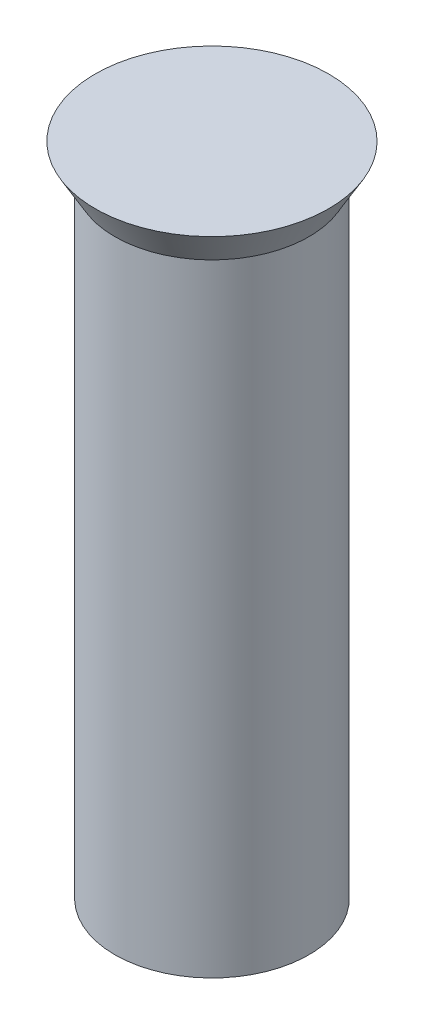
SolidWorks part; units mm, degrees
ref_plane "Front" through (0, 0, 0) normal (0, 0, 1) x (1, 0, 0)
ref_plane "Top" through (0, 0, 0) normal (0, 1, 0) x (1, 0, 0)
ref_plane "Right" through (0, 0, 0) normal (1, 0, 0) x (0, 0, -1)
sketch "Sketch1" plane through (0, 0, 0) normal (0, 0, 1) x (1, 0, 0)
  line L0 (0, 0) -> (0, 6.35) construction
  line L1 (0, 6.35) -> (1.1303, 6.35)
  line L2 (1.1303, 6.35) -> (0.9398, 6.02)
  line L3 (0.9398, 6.02) -> (0.9398, 0)
  line L4 (0.9398, 0) -> (0, 0)
  line L5 (0, 0) -> (0, 6.35)
  dimension "D1" = 1.8796
  dimension "D2" = 2.2606
  dimension "D3" = 30
  dimension "D4" = 0.33
  dimension "D5" = 6.35
revolve "Revolve1" add sketch "Sketch1" angle 360 about L0
